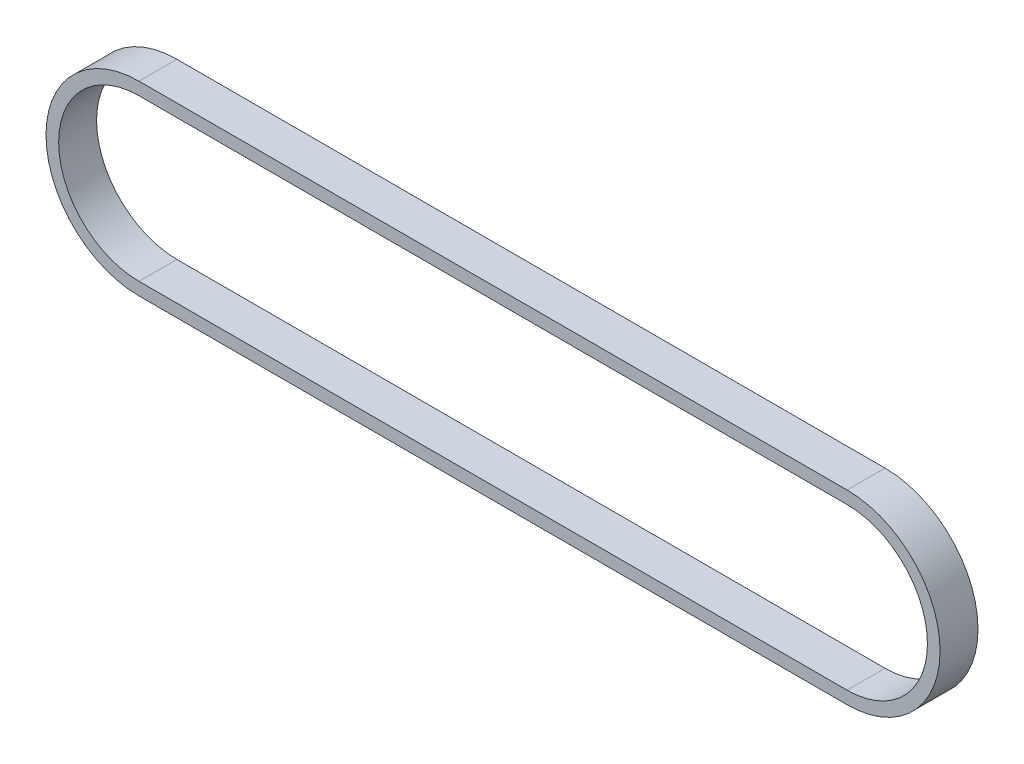
SolidWorks part; units mm, degrees
ref_plane "Front Plane" through (0, 0, 0) normal (0, 0, 1) x (1, 0, 0)
ref_plane "Top Plane" through (0, 0, 0) normal (0, 1, 0) x (1, 0, 0)
ref_plane "Right Plane" through (0, 0, 0) normal (1, 0, 0) x (0, 0, -1)
sketch "Sketch1" plane through (0, 0, 0) normal (0, 0, 1) x (1, 0, 0)
  line L0 (0, 0) -> (112, 0) construction
  line L1 (0, 12.71) -> (112, 12.71)
  line L2 (0, -12.71) -> (112, -12.71)
  line L3 (0, 14.71) -> (112, 14.71)
  line L4 (0, -14.71) -> (112, -14.71)
  arc A0 (0, 12.71) -> (0, -12.71) centre (0, 0) ccw
  arc A1 (112, -12.71) -> (112, 12.71) centre (112, 0) ccw
  arc A2 (112, -14.71) -> (112, 14.71) centre (112, 0) ccw
  arc A3 (0, 14.71) -> (0, -14.71) centre (0, 0) ccw
  point P3 (56, 0)
  dimension "D2" = 12.71
  dimension "D3" = 2
  dimension "D1" = 112
extrude "Boss-Extrude1" add sketch "Sketch1" along normal blind 6
